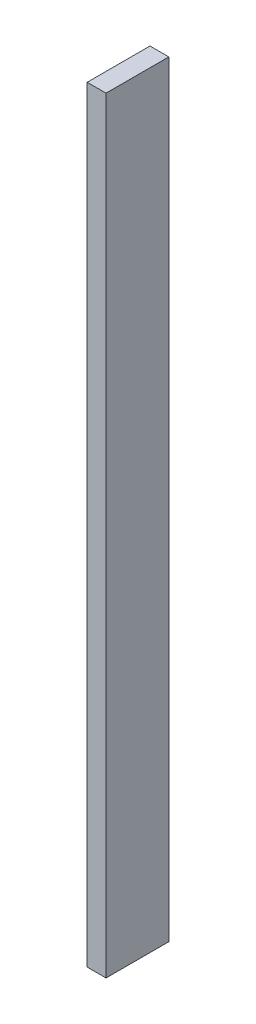
SolidWorks part; units mm, degrees
material "Rubber"
ref_plane "Front Plane" through (0, 0, 0) normal (1, 0, 0) x (0, 1, 0)
ref_plane "Top Plane" through (0, 0, 0) normal (0, 0, 1) x (0, 1, 0)
ref_plane "Right Plane" through (0, 0, 0) normal (0, 1, 0) x (-1, 0, 0)
sketch "Sketch1" plane through (0, 0, 0) normal (0, 0, 1) x (0, 1, 0)
  line L1 (-61, -1.5) -> (61, -1.5)
  line L2 (-61, -1.5) -> (-61, 1.5)
  line L3 (-61, 1.5) -> (61, 1.5)
  line L4 (61, -1.5) -> (61, 1.5)
  line L5 (-61, -1.5) -> (61, 1.5) construction
  line L6 (-61, 1.5) -> (61, -1.5) construction
  point P0 (0, 0)
  dimension "D1" = 3
  dimension "D2" = 122
extrude "Boss-Extrude1" add sketch "Sketch1" along normal blind 10
